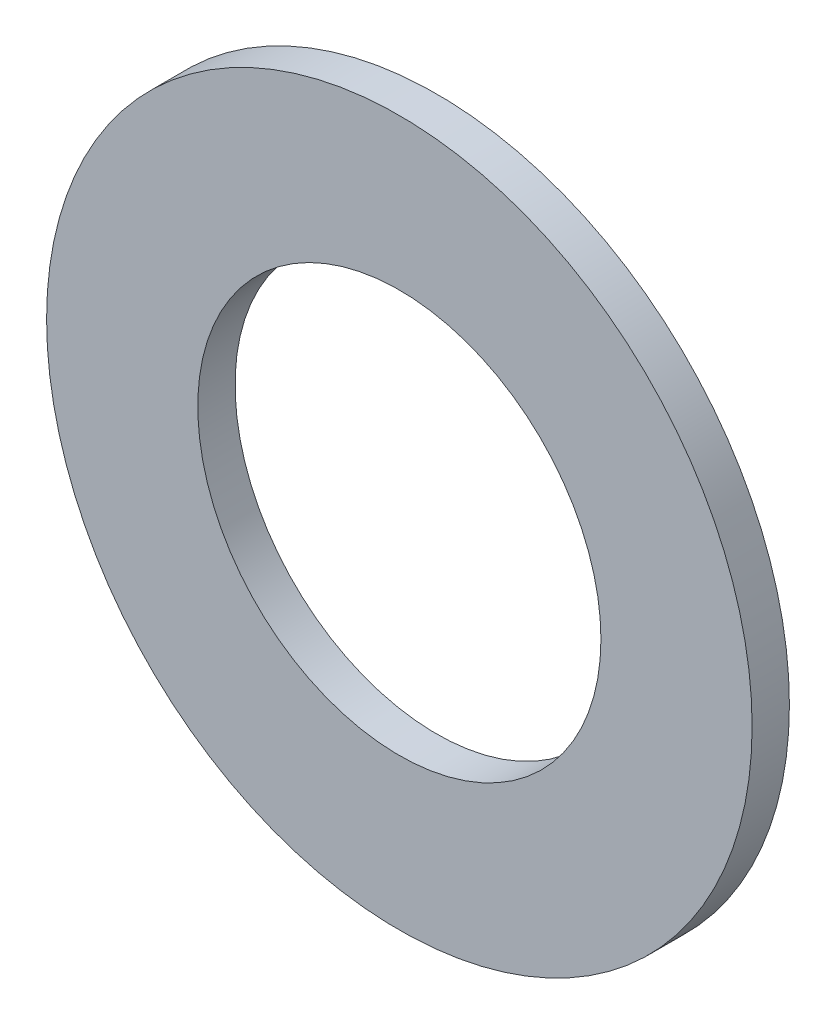
SolidWorks part; units mm, degrees
material "ABS"
ref_plane "前视基准面" through (0, 0, 0) normal (0, 0, 1) x (1, 0, 0)
ref_plane "上视基准面" through (0, 0, 0) normal (0, 1, 0) x (1, 0, 0)
ref_plane "右视基准面" through (0, 0, 0) normal (1, 0, 0) x (0, 0, -1)
other "Configuration Table"
sketch "草图1" plane through (0, 0, 0) normal (0, 0, 1) x (1, 0, 0)
  circle A0 centre (0, 0) radius 10
  circle A1 centre (0, 0) radius 17.5
  dimension "D1" = 35
  dimension "D2" = 20
extrude "凸台-拉伸1" add sketch "草图1" along normal blind 1.85
